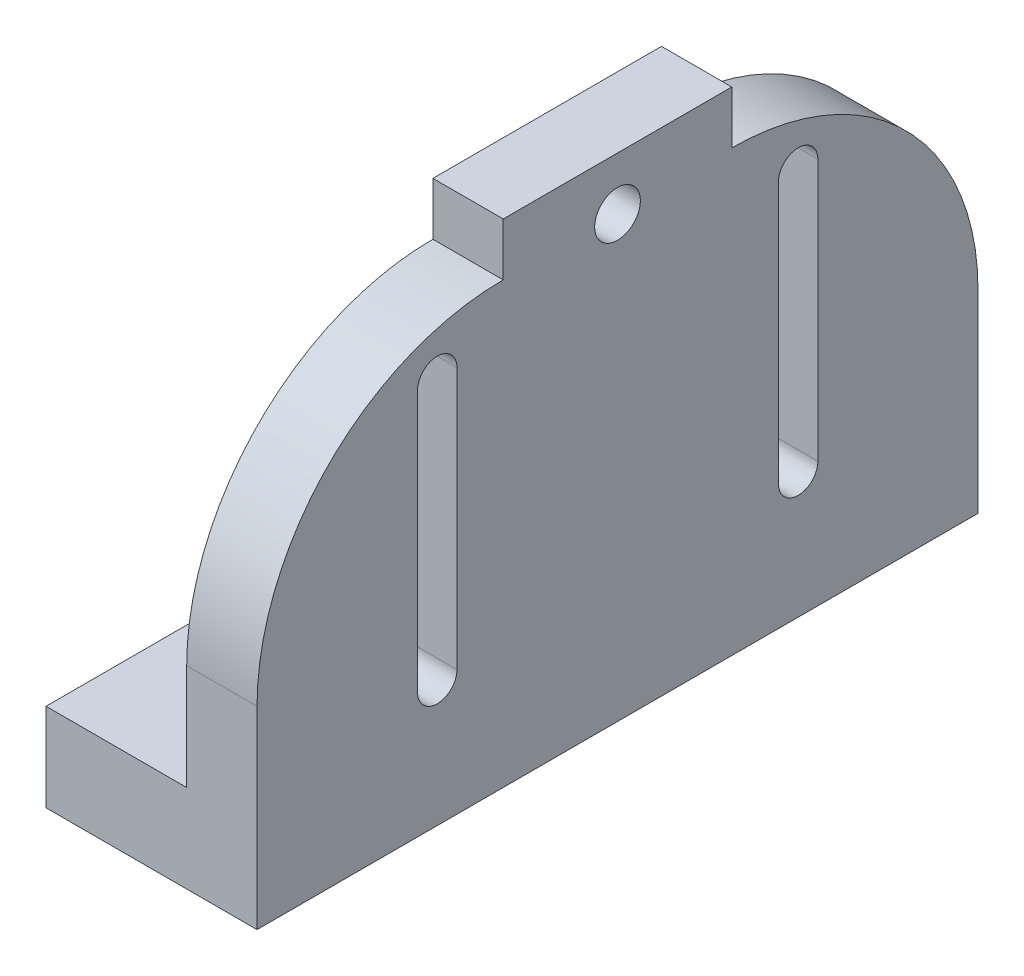
SolidWorks part; units mm, degrees
material "ABS"
ref_plane "Front Plane" through (0, 0, 0) normal (0, 0, 1) x (1, 0, 0)
ref_plane "Top Plane" through (0, 0, 0) normal (0, 1, 0) x (1, 0, 0)
ref_plane "Right Plane" through (0, 0, 0) normal (1, 0, 0) x (0, 0, -1)
sketch "Sketch1" plane through (0, 0, 0) normal (0, 1, 0) x (1, 0, 0)
  line L1 (0, 0) -> (15.24, 0)
  line L2 (0, 0) -> (0, 52.07)
  line L3 (0, 52.07) -> (15.24, 52.07)
  line L4 (15.24, 0) -> (15.24, 52.07)
  dimension "D1" = 15.24
  dimension "D2" = 52.07
extrude "Boss-Extrude1" add sketch "Sketch1" along normal blind 6.35
sketch "Sketch2" plane through (0, 6.35, 0) normal (0, 1, 0) x (1, 0, 0)
  line L0 (0, 0) -> (15.24, 0) construction
  line L1 (15.24, 52.07) -> (10.16, 52.07)
  line L2 (15.24, 52.07) -> (15.24, 0)
  line L3 (15.24, 0) -> (10.16, 0)
  line L4 (10.16, 52.07) -> (10.16, 0)
  dimension "D1" = 5.08
extrude "Boss-Extrude2" add sketch "Sketch2" along normal blind 25.4
sketch "Sketch3" plane through (15.24, 0, 0) normal (1, 0, 0) x (0, 0, -1)
  line L1 (14.4399, 27.94) -> (14.4399, 9.0424)
  line L2 (11.5951, 27.94) -> (11.5951, 9.0424)
  line L4 (0, 31.75) -> (52.07, 31.75) construction
  line L5 (13.0175, 31.75) -> (13.0175, 0) construction
  line L6 (8.382, 0) -> (-8.382, 0) construction
  line L7 (0, 31.75) -> (26.035, 31.75) construction
  line L8 (0, 31.75) -> (0, 0) construction
  line L9 (0, 0) -> (26.035, 0) construction
  line L10 (26.035, 31.75) -> (26.035, 0) construction
  line L11 (52.07, 31.75) -> (52.07, 0) construction
  line L12 (26.035, 31.75) -> (52.07, 31.75) construction
  line L13 (26.035, 31.75) -> (26.035, 0) construction
  line L14 (26.035, 0) -> (52.07, 0) construction
  line L15 (52.07, 31.75) -> (52.07, 0) construction
  line L16 (39.0525, 31.75) -> (39.0525, 0) construction
  line L17 (40.5052, 27.94) -> (40.5052, 9.0424)
  line L18 (37.6604, 27.94) -> (37.6604, 9.0424)
  arc A0 (14.4399, 27.94) -> (11.5951, 27.94) centre (13.0175, 27.94) ccw
  arc A1 (11.5951, 9.0424) -> (14.4399, 9.0424) centre (13.0175, 9.0424) ccw
  arc A2 (40.5052, 27.94) -> (37.6604, 27.94) centre (39.0828, 27.94) ccw
  arc A3 (37.6604, 9.0424) -> (40.5052, 9.0424) centre (39.0828, 9.0424) ccw
  point P11 (13.0175, 7.62)
  point P31 (39.0828, 7.62)
  dimension "D1" = 2.8448
  dimension "D2" = 7.62
  dimension "D3" = 26.035
  dimension "D4" = 3.81
extrude "Cut-Extrude1" cut sketch "Sketch3" against normal blind 8.382
sketch "Sketch4" plane through (0, 6.35, 0) normal (0, 1, 0) x (1, 0, 0)
  line L0 (10.16, 52.07) -> (0, 52.07) construction
  line L1 (5.08, 38.735) -> (5.08, 13.335) construction
  line L2 (0, 52.07) -> (0, 0) construction
  circle A0 centre (5.08, 38.735) radius 1.651
  circle A1 centre (5.08, 13.335) radius 1.651
  point P4 (5.08, 52.07)
  point P7 (0, 26.035)
  point P10 (5.08, 26.035)
  dimension "D1" = 3.302
  dimension "D2" = 25.4
extrude "Cut-Extrude2" cut sketch "Sketch4" against normal blind 8.382
fillet "Fillet1" radius 17.78 2 edges at (12.7, 31.75, 0) (12.7, 31.75, -52.07)
sketch "Sketch6" plane through (0, 31.75, 0) normal (0, 1, 0) x (1, 0, 0)
  line L1 (15.24, 34.29) -> (10.16, 34.29)
  line L2 (15.24, 34.29) -> (15.24, 17.78)
  line L3 (15.24, 17.78) -> (10.16, 17.78)
  line L4 (10.16, 34.29) -> (10.16, 17.78)
extrude "Boss-Extrude3" add sketch "Sketch6" along normal blind 3.81
sketch "Sketch7" plane through (10.16, 0, 0) normal (-1, 0, 0) x (0, 0, 1)
  line L0 (-34.29, 35.56) -> (-17.78, 35.56) construction
  circle A0 centre (-26.035, 31.75) radius 1.651
  point P4 (-26.035, 35.56)
  dimension "D1" = 3.302
extrude "Cut-Extrude3" cut sketch "Sketch7" against normal blind 14.478
